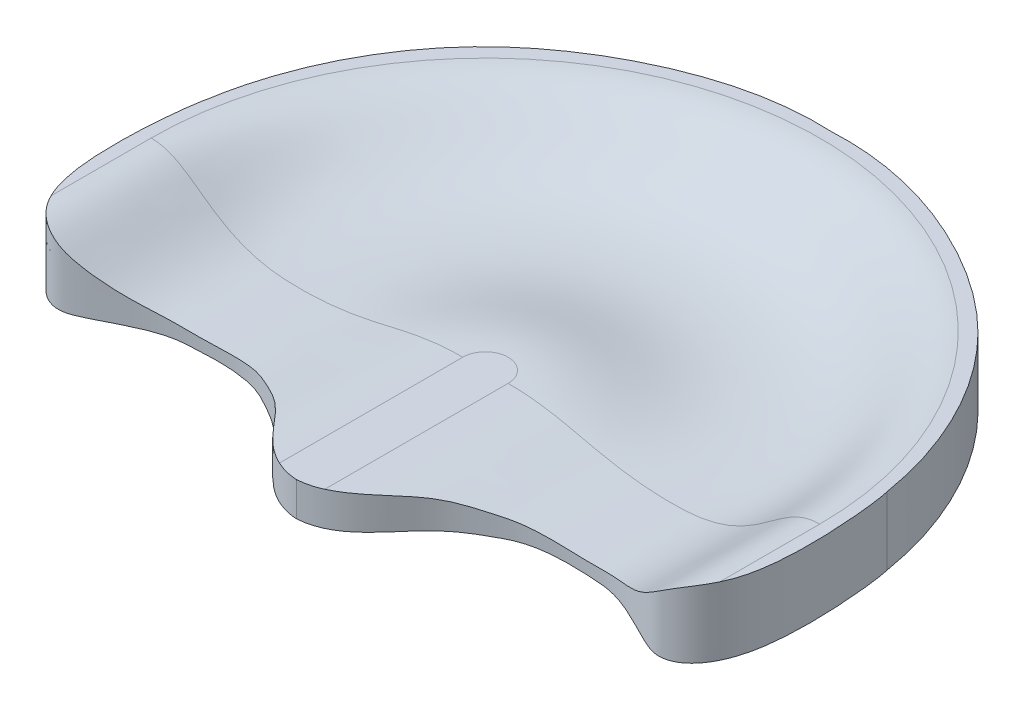
SolidWorks part; units mm, degrees
ref_plane "Front Plane" through (0, 0, 0) normal (0, 0, 1) x (1, 0, 0)
ref_plane "Top Plane" through (0, 0, 0) normal (0, 1, 0) x (1, 0, 0)
ref_plane "Right Plane" through (0, 0, 0) normal (1, 0, 0) x (0, 0, -1)
sketch "Sketch2" plane through (0, 0, 0) normal (0, 1, 0) x (1, 0, 0)
sketch "Sketch3" plane through (0, 0, 0) normal (0, 1, 0) x (1, 0, 0)
  line L0 (0, 0) -> (0, 159.1899) construction
  line L1 (0, 0) -> (0, -140.5301) construction
  line L2 (0, 0) -> (-190.5, 0) construction
  line L3 (0, 0) -> (190.5, 0) construction
  spline S0 degree 3 poles (-190.5, 0) (-184.3927, 37.537) (-157.2613, 93.9641) (-82.3875, 146.6227) (-31.3114, 160.7999) (0, 159.1899) knots 0 0 0 0 0.424401 0.65637 1 1 1 1
  spline S1 degree 3 poles (-190.5, 0) (-192.064, -4.9635) (-201.9672, -83.3146) (-174.6966, -109.29) (-151.6301, -100.568) (-131.4108, -87.7198) (-96.8436, -85.3754) (-78.6925, -86.2588) (-58.8335, -96.8794) (-37.3059, -109.9358) (-21.3496, -139.1148) (0, -140.5301) knots 0 0 0 0 0.166997 0.292321 0.319633 0.426735 0.458914 0.609242 0.64191 0.766802 1 1 1 1
  spline S2 degree 3 poles (190.5, 0) (192.064, -4.9635) (201.9672, -83.3146) (174.6966, -109.29) (151.6301, -100.568) (131.4108, -87.7198) (96.8436, -85.3754) (78.6925, -86.2588) (58.8335, -96.8794) (37.3059, -109.9358) (21.3496, -139.1148) (0, -140.5301) knots 0 0 0 0 0.166997 0.292321 0.319633 0.426735 0.458914 0.609242 0.64191 0.766802 1 1 1 1
  spline S3 degree 3 poles (190.5, 0) (184.3927, 37.537) (157.2613, 93.9641) (82.3875, 146.6227) (31.3114, 160.7999) (0, 159.1899) knots 0 0 0 0 0.424401 0.65637 1 1 1 1
  dimension "D1" = 381
  dimension "D2" = 299.72
  dimension "D3" = 159.1899
  dimension "D4" = 86.8953
  dimension "D5" = 104.4979
  dimension "D6" = 29.1616
  dimension "D7" = 92.2742
  dimension "D8" = 108.411
  dimension "D9" = 67.4883
  dimension "D10" = 43.7314
  dimension "D11" = 117.6915
  dimension "D12" = 162.2568
  dimension "D13" = 89.4522
  dimension "D14" = 140.1036
  dimension "D15" = 175.0666
  dimension "D16" = 50.2669
  dimension "D17" = 101.3666
  dimension "D18" = 138.1225
  dimension "D19" = 155.1557
  dimension "D20" = 192.0074
  dimension "D21" = 193.9268
  dimension "D23" = 76.6666
extrude "Boss-Extrude1" add sketch "Sketch3" along normal blind 6.35 from surface at 0 starting at plane "Top Plane"
sketch "Sketch5" plane through (0, 0, 0) normal (0, -1, 0) x (1, 0, 0)
  line L0 (0, 0) -> (0, -20.32) construction
  line L1 (25.4, -45.72) -> (-25.4, -45.72)
  line L2 (25.4, -45.72) -> (25.4, 5.08)
  line L3 (25.4, 5.08) -> (-25.4, 5.08)
  line L4 (-25.4, -45.72) -> (-25.4, 5.08)
  line L5 (25.4, -45.72) -> (-25.4, 5.08) construction
  line L6 (25.4, 5.08) -> (-25.4, -45.72) construction
  point P0 (0, -20.32)
  point P3 (0, -20.32)
  dimension "D1" = 20.32
  dimension "D2" = 50.8
  dimension "D3" = 50.8
hole_wizard "1/4 (0.25) Diameter Hole1" positions "Sketch6" profile "Sketch7" hole size "1/4" standard "ANSI Inch" end condition through all
sketch "Sketch6" plane through (0, 0, 0) normal (0, -1, 0) x (-1, 0, 0)
  point P0 (-25.4, 45.72)
  point P3 (25.4, 45.72)
  point P6 (25.4, -5.08)
  point P9 (-25.4, -5.08)
sketch "Sketch7" plane through (25.4, 0, -45.72) normal (1, 0, 0) x (0, 0, -1)
  line L0 (0, 0) -> (0, 6.35)
  line L1 (0, 6.35) -> (3.175, 6.35)
  line L2 (3.175, 6.35) -> (3.175, 0)
  line L5 (3.175, 0) -> (0, 0)
  line L11 (0, -6.35) -> (0, 107.95) construction
  dimension "Thru Hole Dia." = 6.35
  dimension "Thru Hole Depth" = 6.35
split line "Split Line2"
sketch "Sketch9" plane through (0, 6.35, 0) normal (0, 1, 0) x (1, 0, 0)
  line L0 (-181.6913, 0) -> (-171.8472, 0) construction
  line L2 (-187.357, -34.5171) -> (-187.357, -163.3551)
  line L3 (187.357, -34.5171) -> (187.357, -159.7944)
  arc A1 (187.357, -34.5171) -> (-187.357, -34.5171) centre (0, -34.5171) ccw
  point P12 (0, 152.8399)
  point P17 (184.15, 0)
  dimension "D2" = 6.35
  dimension "D1" = 6.35
ref_plane "Plane1" through (0, 0, 159.7944) normal (0, 0, 1) x (1, 0, 0)
sketch "Sketch14" plane through (0, 0, 159.7944) normal (0, 0, 1) x (1, 0, 0)
  line L0 (187.357, 6.35) -> (187.357, 38.1)
  line L2 (213.6239, 38.1) -> (160.1804, 38.1) construction
  line L3 (63.3521, 19.05) -> (-13.9427, 19.05) construction
  line L5 (12.7, 19.05) -> (12.7, 6.35)
  line L6 (12.7, 6.35) -> (187.357, 6.35)
  line L7 (187.357, 6.35) -> (-187.357, 6.35) construction
  line L8 (-200181.6913, 6.35) -> (199828.1528, 6.35) construction
  line L11 (151.7074, 6.6675) -> (95.3126, 6.6675) construction
  spline S0 degree 3 poles (12.7, 19.05) (43.942, 19.05) (62.693, 6.893) (152.9669, 6.0445) (164.497, 38.1) (187.357, 38.1) knots 0 0 0 0 0.419038 0.519038 1 1 1 1
  dimension "D4" = 104.14
  dimension "D5" = 76.2
  dimension "D7" = 254
  dimension "D2" = 31.75
  dimension "D3" = 12.7
  dimension "D1" = 12.7
  dimension "D6" = 104.14
  dimension "D8" = 0.3175
sweep "Sweep3" add profiles "Sketch14" path "Sketch9"
sketch "Sketch16" plane through (0, 0, 0) normal (0, -1, 0) x (1, 0, 0)
  line L6 (-187.357, 163.3551) -> (-187.357, 90.603)
  line L7 (-12.7, 137.2764) -> (-12.7, 163.3551)
  line L8 (-12.7, 163.3551) -> (-187.357, 163.3551)
  line L9 (-187.357, 163.3551) -> (-187.357, 90.603)
  line L10 (-12.7, 137.2764) -> (-12.7, 163.3551)
  line L11 (-12.7, 163.3551) -> (-187.357, 163.3551)
  line L18 (12.7, 159.7944) -> (12.7, 137.2764)
  line L19 (187.357, 90.603) -> (187.357, 159.7944)
  line L20 (187.357, 159.7944) -> (12.7, 159.7944)
  line L21 (12.7, 159.7944) -> (12.7, 137.2764)
  line L22 (187.357, 90.603) -> (187.357, 159.7944)
  line L23 (187.357, 159.7944) -> (12.7, 159.7944)
  spline S6 degree 3 poles (2464.61, -1157.9319) (-315.8488, -580.5228) (-249.9129, 137.731) (-151.6301, 100.568) (-131.4108, 87.7198) (-96.8436, 85.3754) (-78.6925, 86.2588) (-58.8335, 96.8794) (14.7404, 141.5017) (36.5922, 412.8888) (1633.9557, -2362.8358) knots -0.67997 -0.67997 -0.67997 -0.67997 0.292321 0.319633 0.426735 0.458914 0.609242 0.64191 0.766802 1.94472 1.94472 1.94472 1.94472 only from (-187.357, 90.603) to (-12.7, 137.2764)
  spline S7 degree 3 poles (-187.357, 90.603) (-182.0225, 101.4567) (-171.7449, 108.1739) (-151.6301, 100.568) (-131.4108, 87.7198) (-96.8436, 85.3754) (-78.6925, 86.2588) (-58.8335, 96.8794) (-40.149, 108.2115) (-26.027, 131.062) (-12.7, 137.2764) knots 0.200234 0.200234 0.200234 0.200234 0.292321 0.319633 0.426735 0.458914 0.609242 0.64191 0.766802 0.948394 0.948394 0.948394 0.948394
  spline S10 degree 3 poles (-1633.9531, -2362.8313) (-36.5922, 412.8886) (-14.7404, 141.5017) (58.8335, 96.8794) (78.6925, 86.2588) (96.8436, 85.3754) (131.4108, 87.7198) (151.6301, 100.568) (249.913, 137.731) (315.8489, -580.524) (-2464.6176, -1157.9334) knots -0.944719 -0.944719 -0.944719 -0.944719 0.233198 0.35809 0.390758 0.541086 0.573265 0.680367 0.707679 1.679971 1.679971 1.679971 1.679971 only from (12.7, 137.2764) to (187.357, 90.603)
  spline S11 degree 3 poles (12.7, 137.2764) (26.027, 131.062) (40.149, 108.2115) (58.8335, 96.8794) (78.6925, 86.2588) (96.8436, 85.3754) (131.4108, 87.7198) (151.6301, 100.568) (171.7449, 108.1739) (182.0225, 101.4567) (187.357, 90.603) knots 0.051606 0.051606 0.051606 0.051606 0.233198 0.35809 0.390758 0.541086 0.573265 0.680367 0.707679 0.799766 0.799766 0.799766 0.799766
  dimension "D1" = 0
  dimension "D2" = 0
extrude "Cut-Extrude3" cut sketch "Sketch16" against normal through all
fillet "Fillet1" [suppressed] radius 6.35
sketch "Sketch18" plane through (0, 6.35, 0) normal (0, 1, 0) x (1, 0, 0)
  line L4 (-187.357, -90.603) -> (-187.357, -34.5171)
  line L8 (-187.357, -90.603) -> (-187.357, -34.5171)
  line L10 (187.357, -34.5171) -> (187.357, -90.603)
  line L11 (187.357, -34.5171) -> (187.357, -90.603)
  arc A2 (187.357, -34.5171) -> (-187.357, -34.5171) centre (0, -34.5171) ccw
  arc A5 (187.357, -34.5171) -> (-187.357, -34.5171) centre (0, -34.5171) ccw
  spline S8 degree 3 poles (-995.7139, -3917.4533) (-12.0231, 529.3059) (-518.8316, -663.7556) (379.0469, 344.1528) (-2707.5322, 2933.0894) knots -0.586575 -0.586575 -0.586575 -0.586575 0.166997 1.26947 1.26947 1.26947 1.26947 only from (-190.5, 0) to (-187.357, -90.603)
  spline S9 degree 3 poles (2707.4536, 2933.0235) (-379.0379, 344.1427) (518.8297, -663.7503) (12.0224, 529.3076) (995.719, -3917.4764) knots -0.269461 -0.269461 -0.269461 -0.269461 0.833003 1.586576 1.586576 1.586576 1.586576 only from (187.357, -90.603) to (190.5, 0)
  spline S10 degree 3 poles (-2685.9946, 2588.5322) (-86.9259, -1057.8795) (400.6891, -77.2381) (-118.3676, 287.8132) (-617.6631, -57.1843) (79.2205, -3772.4557) knots -3.251174 -3.251174 -3.251174 -3.251174 0.424401 0.65637 3.681246 3.681246 3.681246 3.681246 only from (190.5, 0) to (0, 159.1899)
  spline S11 degree 3 poles (-79.2172, -3772.4383) (617.6616, -57.1833) (118.3672, 287.813) (-400.6896, -77.2384) (86.9274, -1057.8825) (2686.0075, 2588.5503) knots -2.681241 -2.681241 -2.681241 -2.681241 0.34363 0.575599 4.251181 4.251181 4.251181 4.251181 only from (0, 159.1899) to (-190.5, 0)
  spline S12 degree 3 poles (-190.5, 0) (-192.064, -4.9635) (-198.8475, -58.6326) (-189.2824, -86.6855) (-187.357, -90.603) knots 0 0 0 0 0.166997 0.200234 0.200234 0.200234 0.200234
  spline S13 degree 3 poles (187.357, -90.603) (189.2824, -86.6855) (198.8475, -58.6326) (192.064, -4.9635) (190.5, 0) knots 0.799766 0.799766 0.799766 0.799766 0.833003 1 1 1 1
  spline S14 degree 3 poles (190.5, 0) (184.3927, 37.537) (157.2613, 93.9641) (82.3875, 146.6227) (31.3114, 160.7999) (0, 159.1899) knots 0 0 0 0 0.424401 0.65637 1 1 1 1
  spline S15 degree 3 poles (0, 159.1899) (-31.3114, 160.7999) (-82.3875, 146.6227) (-157.2613, 93.9641) (-184.3927, 37.537) (-190.5, 0) knots 0 0 0 0 0.34363 0.575599 1 1 1 1
  dimension "D1" = 0
extrude "Boss-Extrude2" add sketch "Sketch18" along normal up to vertex (31.75 mm away)
sketch "Sketch20" plane through (0, 6.35, 0) normal (0, 1, 0) x (1, 0, 0)
  line L4 (-12.7, -34.5171) -> (-12.7, -137.2764)
  line L5 (12.7, -137.2764) -> (12.7, -34.5171)
  line L6 (-12.7, -34.5171) -> (-12.7, -137.2764)
  line L7 (12.7, -137.2764) -> (12.7, -34.5171)
  arc A2 (12.7, -34.5171) -> (-12.7, -34.5171) centre (0, -34.5171) ccw
  arc A3 (12.7, -34.5171) -> (-12.7, -34.5171) centre (0, -34.5171) ccw
  spline S4 degree 3 poles (-1487.8148, -2742.7117) (1260.9426, 2724.9636) (-1403.1617, -2915.3255) (1636.6112, 2367.4506) knots -0.293747 -0.293747 -0.293747 -0.293747 1.945372 1.945372 1.945372 1.945372 only from (-12.7, -137.2764) to (0, -140.5301)
  spline S5 degree 3 poles (-1636.6158, 2367.4586) (1403.1791, -2915.3569) (-1260.9698, 2725.0211) (1487.8548, -2742.7913) knots -0.945373 -0.945373 -0.945373 -0.945373 1.293758 1.293758 1.293758 1.293758 only from (0, -140.5301) to (12.7, -137.2764)
  spline S6 degree 3 poles (-12.7, -137.2764) (-8.9126, -139.0424) (-4.7246, -140.2169) (0, -140.5301) knots 0.948394 0.948394 0.948394 0.948394 1 1 1 1
  spline S7 degree 3 poles (0, -140.5301) (4.7246, -140.2169) (8.9126, -139.0424) (12.7, -137.2764) knots 0 0 0 0 0.051606 0.051606 0.051606 0.051606
  dimension "D1" = 0
extrude "Boss-Extrude3" add sketch "Sketch20" along normal blind 12.7
equation "\"Wall Height\"= 1.5"
equation "\"D1@Boss-Extrude1\"=\"Min Thickness\""
equation "\"Bracket Alignment\"= .80"
equation "\"D1@Sketch5\"=\"Bracket Alignment\""
equation "\"Min Thickness\"= .25"
equation "\"D2@Sketch14\"=\"Wall Height\"-\"Min Thickness\""
equation "\"Center Thickness\"= .75"
equation "\"D1@Sketch14\"=\"Center Thickness\"-\"Min Thickness\""
equation "\"D1@Boss-Extrude3\"=\"Center Thickness\"-\"Min Thickness\""
equation "\"D1@Boss-Extrude2\"=\"Wall Height\"-\"Min Thickness\""
equation "\"Contour Strenght Center\"= 4"
equation "\"Contour Strength Middle\"= 10"
equation "\"Contour Strength Lip\"= 1"
equation "\"Contour Offset Middle\"= 4.1"
equation "\"D4@Sketch14\"=\"Contour Offset Middle\""
equation "\"D6@Sketch14\"=\"Contour Offset Middle\""
equation "\"D7@Sketch14\"=\"Contour Strength Middle\""
equation "\"D8@Sketch14\"=.01*(\"Wall Height\"-\"Min Thickness\")"
